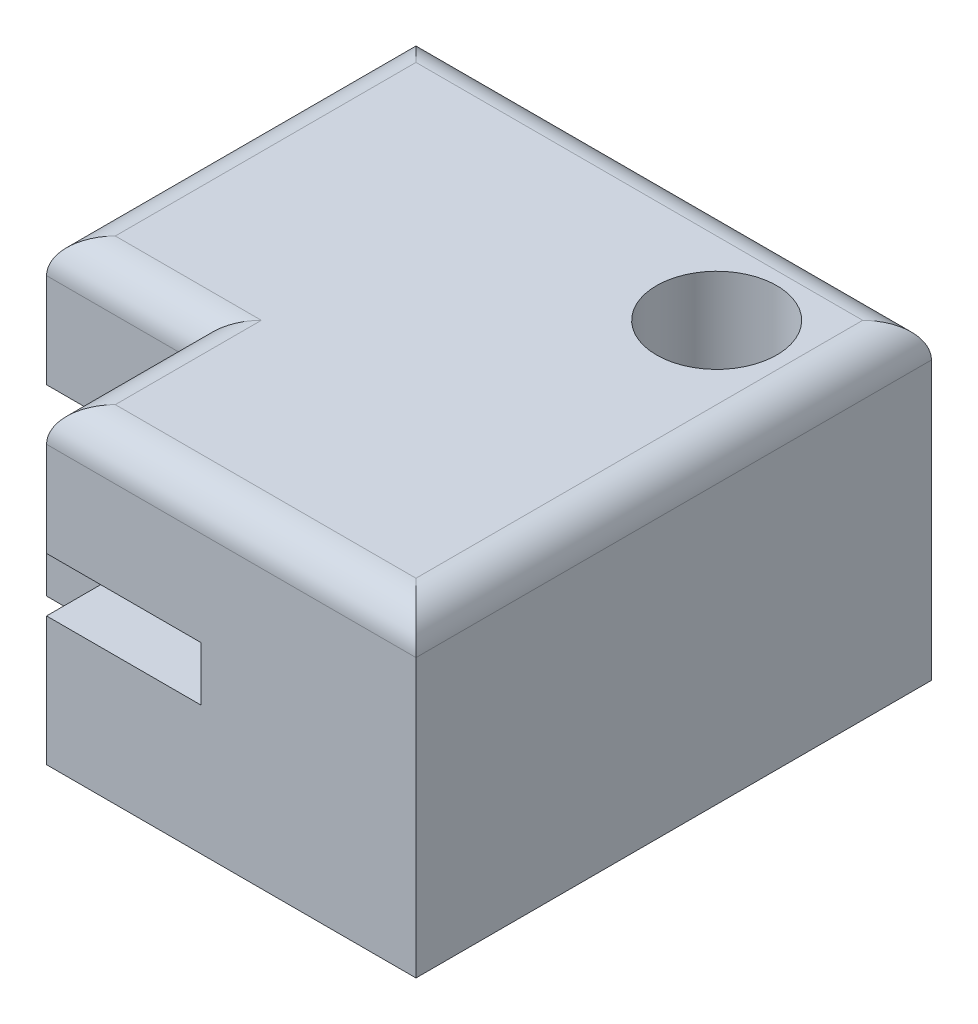
SolidWorks part; units mm, degrees
ref_plane "Front Plane" through (0, 0, 0) normal (0, 0, 1) x (1, 0, 0)
ref_plane "Top Plane" through (0, 0, 0) normal (0, 1, 0) x (1, 0, 0)
ref_plane "Right Plane" through (0, 0, 0) normal (1, 0, 0) x (0, 0, -1)
sketch "Sketch1" plane through (0, 0, 0) normal (0, 1, 0) x (1, 0, 0)
  line L1 (-7.62, -7.62) -> (7.62, -7.62)
  line L2 (-7.62, -7.62) -> (-7.62, 7.62)
  line L3 (-7.62, 7.62) -> (7.62, 7.62)
  line L4 (7.62, -7.62) -> (7.62, 7.62)
  line L5 (-7.62, -7.62) -> (7.62, 7.62) construction
  line L6 (-7.62, 7.62) -> (7.62, -7.62) construction
  point P0 (0, 0)
  dimension "D1" = 15.24
  dimension "D2" = 15.24
extrude "Boss-Extrude1" add sketch "Sketch1" along normal blind 3.81
sketch "Sketch2" plane through (0, 3.81, 0) normal (0, 1, 0) x (1, 0, 0)
  line L0 (-7.62, 7.62) -> (-7.62, 1.27)
  line L1 (-7.62, 7.62) -> (-7.62, -7.62) construction
  line L2 (-7.62, 1.27) -> (1.27, 1.27)
  line L3 (1.27, 1.27) -> (1.27, -7.62)
  line L4 (-7.62, -7.62) -> (7.62, -7.62) construction
  line L5 (1.27, -7.62) -> (7.62, -7.62)
  line L6 (7.62, -7.62) -> (7.62, 7.62)
  line L7 (7.62, 7.62) -> (-7.62, 7.62)
  dimension "D1" = 6.35
  dimension "D2" = 6.35
extrude "Boss-Extrude2" add sketch "Sketch2" along normal blind 1.6002
sketch "Sketch3" plane through (0, 5.4102, 0) normal (0, 1, 0) x (1, 0, 0)
  line L1 (-7.62, -7.62) -> (7.62, -7.62)
  line L2 (-7.62, -7.62) -> (-7.62, 7.62)
  line L3 (-7.62, 7.62) -> (7.62, 7.62)
  line L4 (7.62, -7.62) -> (7.62, 7.62)
  line L5 (-7.62, -7.62) -> (7.62, 7.62) construction
  line L6 (-7.62, 7.62) -> (7.62, -7.62) construction
  point P0 (0, 0)
extrude "Boss-Extrude3" add sketch "Sketch3" along normal blind 3.81
sketch "Sketch4" plane through (0, 9.2202, 0) normal (0, 1, 0) x (1, 0, 0)
  line L0 (-7.62, -7.62) -> (7.62, -7.62) construction
  line L1 (-7.62, -7.62) -> (-3.302, -7.62)
  line L2 (-7.62, -7.62) -> (-7.62, -3.302)
  line L3 (-7.62, -3.302) -> (-3.302, -3.302)
  line L4 (-3.302, -7.62) -> (-3.302, -3.302)
  dimension "D1" = 4.318
  dimension "D2" = 4.318
extrude "Cut-Extrude1" cut sketch "Sketch4" against normal through all
sketch "Sketch5" plane through (0, 9.2202, 0) normal (0, 1, 0) x (1, 0, 0)
  line L0 (7.62, -7.62) -> (7.62, 7.62) construction
  line L1 (7.62, 7.62) -> (-7.62, 7.62) construction
  circle A0 centre (4.445, 4.445) radius 1.778
  dimension "D1" = 3.556
  dimension "D2" = 3.175
  dimension "D3" = 3.175
extrude "Cut-Extrude2" cut sketch "Sketch5" against normal through all
fillet "Fillet1" radius 1.016 6 edges at (-7.62, 9.2202, -2.159) (0, 9.2202, -7.62) (7.62, 9.2202, 0) (2.159, 9.2202, 7.62) (-3.302, 9.2202, 5.461) (-5.461, 9.2202, 3.302)
